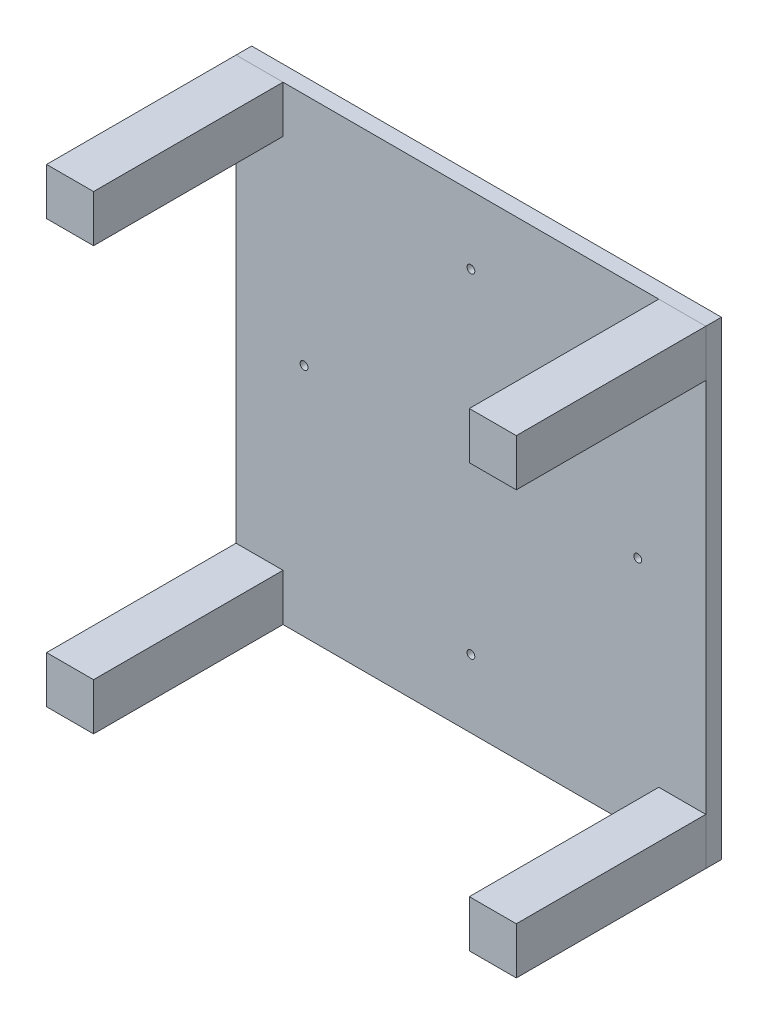
SolidWorks part; units mm, degrees
ref_plane "Front Plane" through (0, 0, 0) normal (0, 0, 1) x (1, 0, 0)
ref_plane "Top Plane" through (0, 0, 0) normal (0, 1, 0) x (1, 0, 0)
ref_plane "Right Plane" through (0, 0, 0) normal (1, 0, 0) x (0, 0, -1)
sketch "Sketch1" plane through (0, 0, 0) normal (0, 0, 1) x (1, 0, 0)
  line L1 (-150, 150) -> (150, 150)
  line L2 (-150, 150) -> (-150, -150)
  line L3 (-150, -150) -> (150, -150)
  line L4 (150, 150) -> (150, -150)
  line L5 (-150, 150) -> (150, -150) construction
  line L6 (-150, -150) -> (150, 150) construction
  circle A0 centre (0, -106.5627) radius 2.5 construction
  circle A1 centre (-106.5627, 0) radius 2.5 construction
  circle A2 centre (106.5627, 0) radius 2.5 construction
  circle A3 centre (0, 106.5627) radius 2.5 construction
  circle A4 centre (0, -106.5627) radius 2.5
  circle A5 centre (-106.5627, 0) radius 2.5
  circle A6 centre (106.5627, 0) radius 2.5
  circle A7 centre (0, 106.5627) radius 2.5
  point P0 (0, 0)
  dimension "D1" = 300
  dimension "D2" = 300
extrude "Boss-Extrude1" add sketch "Sketch1" along normal blind 10
sketch "Sketch2" plane through (0, 0, 10) normal (0, 0, 1) x (1, 0, 0)
  line L0 (0, 193.0934) -> (0, 0) construction
  line L1 (-150, 150) -> (-120, 150)
  line L2 (-150, 150) -> (-150, 120)
  line L3 (-150, 120) -> (-120, 120)
  line L4 (-120, 150) -> (-120, 120)
  line L5 (0, 0) -> (210.2303, 0) construction
  line L6 (120, 150) -> (120, 120)
  line L7 (150, 120) -> (120, 120)
  line L8 (150, 150) -> (150, 120)
  line L9 (150, 150) -> (120, 150)
  line L10 (-150, -150) -> (-150, -120)
  line L11 (-120, -150) -> (-120, -120)
  line L12 (-150, -120) -> (-120, -120)
  line L13 (-150, -150) -> (-120, -150)
  line L14 (150, -150) -> (120, -150)
  line L15 (150, -150) -> (150, -120)
  line L16 (150, -120) -> (120, -120)
  line L17 (120, -150) -> (120, -120)
  dimension "D1" = 30
  dimension "D2" = 30
extrude "Boss-Extrude2" add sketch "Sketch2" along normal blind 121 separate body
